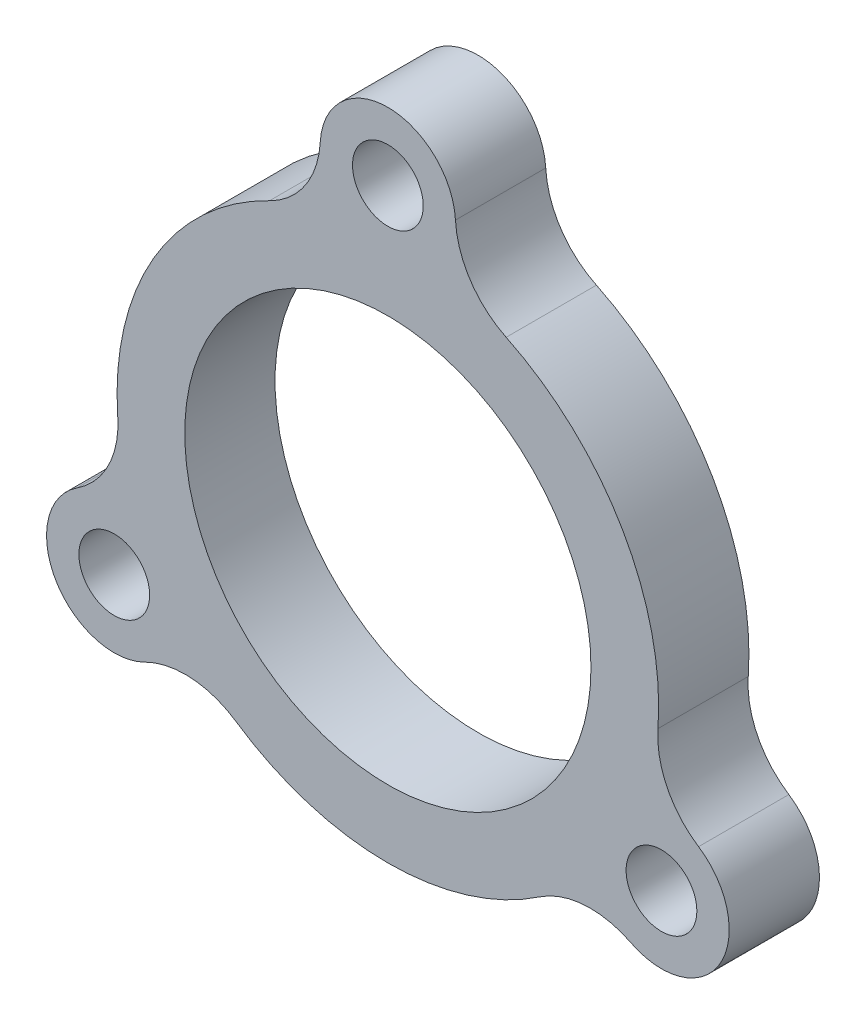
SolidWorks part; units mm, degrees
material "6061-T6 (SS)"
ref_plane "Front Plane" through (0, 0, 0) normal (0, 0, 1) x (1, 0, 0)
ref_plane "Top Plane" through (0, 0, 0) normal (0, 1, 0) x (1, 0, 0)
ref_plane "Right Plane" through (0, 0, 0) normal (1, 0, 0) x (0, 0, -1)
sketch "Sketch2" plane through (0, 0, 0) normal (0, 0, 1) x (1, 0, 0)
  circle A0 centre (0, 0) radius 14.2875
  circle A1 centre (0, 22.225) radius 2.4892
  circle A2 centre (19.2474, -11.1125) radius 2.4892
  circle A3 centre (-19.2474, -11.1125) radius 2.4892
  circle A4 centre (19.2474, -11.1125) radius 4.7625
  circle A5 centre (0, 0) radius 19.05
  circle A6 centre (0, 22.225) radius 4.7625
  circle A7 centre (-19.2474, -11.1125) radius 4.7625
  point P11 (0, 0)
  dimension "D1" = 28.575
  dimension "D2" = 4.9784
  dimension "D6" = 9.525
  dimension "D5" = 38.1
  dimension "D3" = 22.225
  dimension "D4" = 3
extrude "Boss-Extrude1" add sketch "Sketch2" along normal blind 6.35 contours A7 A5 A4 A6 A0 | A5 A6 A1 | A5 A4 A2 | A5 A7 A3 | A5 A6 | A4 A5 | A5 A7
fillet "Fillet2" radius 6.35 6 edges at (-14.6152, -12.2188, 3.175) (-17.8894, -6.5477, 3.175) (-3.2742, 18.7665, 3.175) (3.2742, 18.7665, 3.175) (17.8894, -6.5477, 3.175) (14.6152, -12.2188, 3.175)
